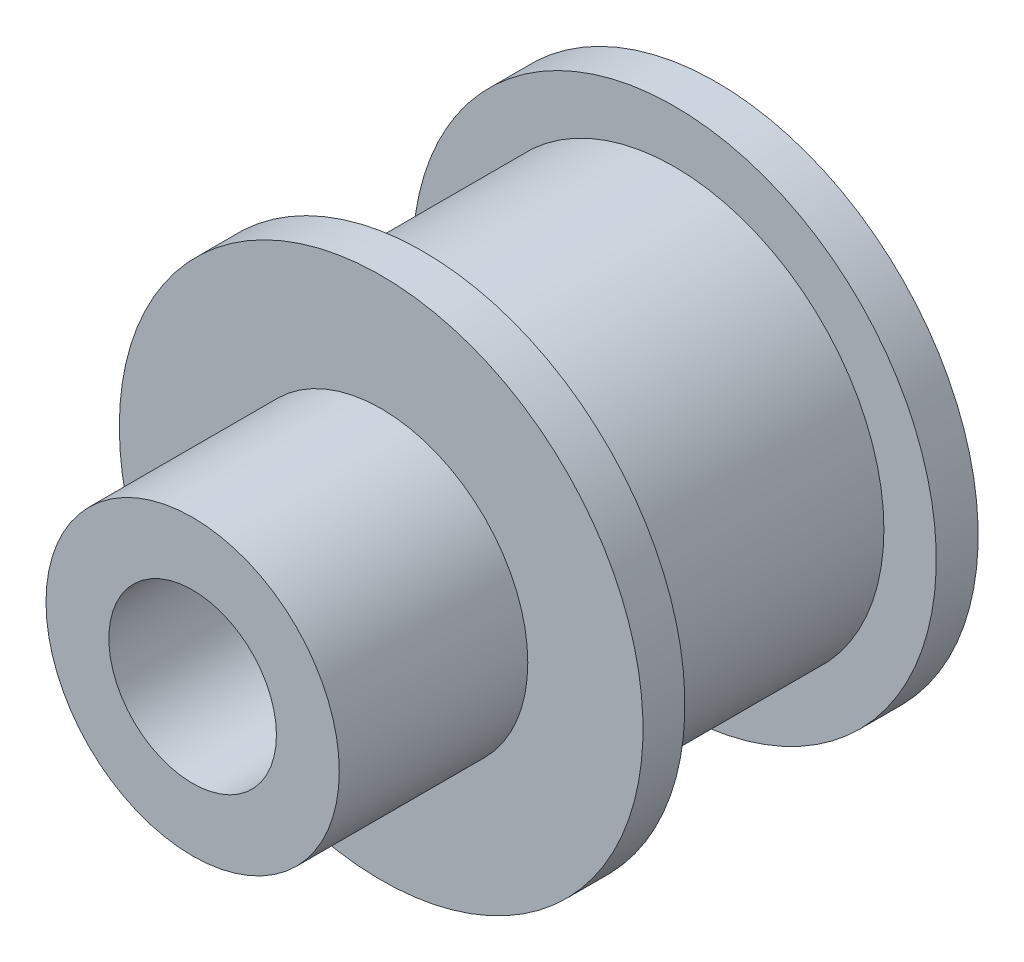
SolidWorks part; units mm, degrees
ref_plane "前视基准面" through (0, 0, 0) normal (0, 0, 1) x (1, 0, 0)
ref_plane "上视基准面" through (0, 0, 0) normal (0, 1, 0) x (1, 0, 0)
ref_plane "右视基准面" through (0, 0, 0) normal (1, 0, 0) x (0, 0, -1)
sketch "草图1" plane through (0, 0, 0) normal (0, 0, 1) x (1, 0, 0)
  circle A0 centre (0, 0) radius 4
  circle A1 centre (0, 0) radius 7
  dimension "D1" = 8
  dimension "D2" = 14
extrude "拉伸1" add sketch "草图1" along normal blind 9
sketch "草图2" plane through (0, 0, 0) normal (0, 0, -1) x (-1, 0, 0)
  circle A0 centre (0, 0) radius 12.5
  circle A1 centre (0, 0) radius 4
  dimension "D1" = 8
  dimension "D2" = 25
extrude "拉伸2" add sketch "草图2" along normal blind 2
sketch "草图3" plane through (0, 0, -2) normal (0, 0, -1) x (-1, 0, 0)
  circle A0 centre (0, 0) radius 10
  dimension "D1" = 20
extrude "拉伸3" add sketch "草图3" along normal blind 12
sketch "草图4" plane through (0, 0, -14) normal (0, 0, -1) x (-1, 0, 0)
  circle A0 centre (0, 0) radius 12.5
  dimension "D1" = 25
extrude "拉伸4" add sketch "草图4" along normal blind 2
sketch "草图5" plane through (0, 0, 9) normal (0, 0, 1) x (1, 0, 0)
  circle A0 centre (0, 0) radius 4
extrude "切除-拉伸1" cut sketch "草图5" against normal through all
